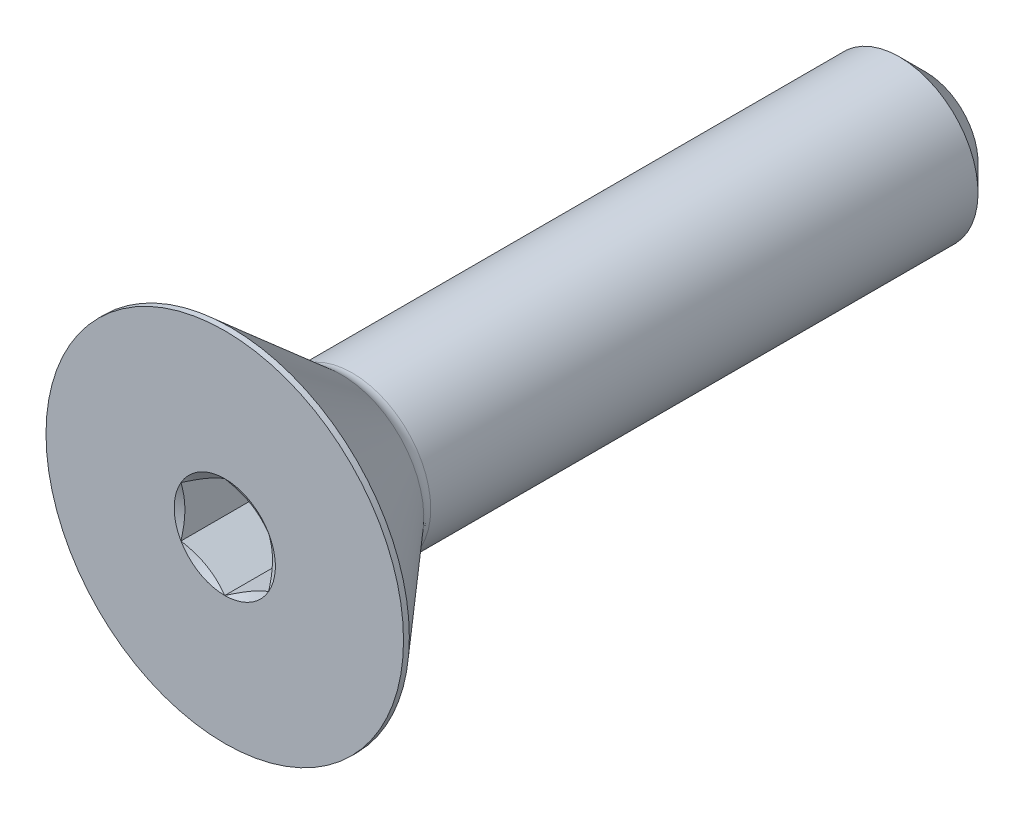
SolidWorks part; units mm, degrees
material "Plain Carbon Steel"
ref_plane "Front" through (0, 0, 0) normal (0, 0, 1) x (1, 0, 0)
ref_plane "Top" through (0, 0, 0) normal (0, 1, 0) x (1, 0, 0)
ref_plane "Right" through (0, 0, 0) normal (1, 0, 0) x (0, 0, -1)
sketch "Sketch1" plane through (0, 0, 0) normal (1, 0, 0) x (0, 0, -1)
  line L0 (0, 3.2385) -> (0.1054, 3.2385) construction
  line L1 (0.1054, 3.2385) -> (2.1082, 1.4975) construction
  line L2 (0, 1.4224) -> (12.7, 1.4224)
  line L3 (12.7, 1.4224) -> (12.7, 0)
  line L4 (12.7, 0) -> (0, 0)
  line L5 (0, 0) -> (0, 3.2385) construction
  line L6 (0, 3.2385) -> (0, -3.2385) construction
  line L7 (12.7, 1.4224) -> (12.7, -1.4224) construction
  line L8 (0, -3.2385) -> (0.1054, -3.2385) construction
  line L9 (0.1054, -3.2385) -> (2.1082, -1.4975) construction
  line L11 (0, 1.4224) -> (0, 0)
  line L12 (2.3091, 1.4224) -> (2.3091, 0) construction
  line L13 (-12.7, 0) -> (-12.7, 1.4224) construction
  arc A1 (2.1082, 1.4975) -> (2.3091, 1.4224) centre (2.3091, 1.7286) ccw construction
  dimension "D1" = 0.1054
  dimension "Min Thread" = 25.4
revolve "Revolve1" add sketch "Sketch1" angle 360 mid plane about L4
ref_plane "Plane2" through (0, 0, 12.7) normal (0, 0, 1) x (1, 0, 0)
chamfer "Chamfer1" distance 0.4763 angle 45 1 edges at (0, 1.4224, -12.7)
sketch "Sketch7" plane through (0, 0, 0) normal (1, 0, 0) x (0, 0, -1)
  line L0 (0, 3.2385) -> (0.1054, 3.2385) construction
  line L1 (0.1054, 3.2385) -> (2.1082, 1.4975) construction
  line L2 (0, 3.2385) -> (0.1054, 3.2385)
  line L3 (0.1054, 3.2385) -> (2.1082, 1.4975)
  line L4 (2.3091, 1.4224) -> (2.3091, 0) construction
  line L5 (2.3091, 1.4224) -> (2.3091, 0)
  line L7 (0, 0) -> (0, 3.2385) construction
  line L8 (0, 0) -> (0, 3.2385)
  line L9 (0, 0) -> (2.3091, 0)
  line L10 (6.985, 0) -> (-6.985, 0) construction
  arc A0 (2.1082, 1.4975) -> (2.3091, 1.4224) centre (2.3091, 1.7286) ccw construction
  arc A1 (2.1082, 1.4975) -> (2.3091, 1.4224) centre (2.3091, 1.7286) ccw
revolve "Revolve2" add sketch "Sketch7" angle 360 mid plane about L9
ref_plane "Plane1" through (0, 0, -2.3091) normal (0, 0, 1) x (1, 0, 0)
sketch "Sketch5" plane through (0, 0, 0) normal (0, 0, 1) x (1, 0, 0)
  line L0 (0, 0) -> (-0.9165, 0) construction
  line L1 (0, 0) -> (-2.7496, 1.5875) construction
  line L2 (0, 0) -> (-2.7496, -1.5875) construction
  line L6 (0, 0.9165) -> (0, 0.7559) construction
  line L7 (0, 0.7559) -> (0, 0.5953) construction
  line L9 (0, 0.9165) -> (-0.7937, 0.4583)
  line L10 (-0.7937, 0.4583) -> (-0.7937, -0.4583)
  line L11 (-0.7937, -0.4583) -> (0, -0.9165)
  line L12 (0, -0.9165) -> (0.7938, -0.4583)
  line L13 (0.7938, -0.4583) -> (0.7937, 0.4583)
  line L14 (0.7937, 0.4583) -> (0, 0.9165)
  circle A0 centre (0, 0) radius 0.9165 construction
  circle A1 centre (0, 0) radius 0.7559 construction
  circle A2 centre (0, 0) radius 0.5953 construction
  circle A3 centre (0, 0) radius 0.7937 construction
  dimension "D3" = 1.1906
  dimension "D4" = 30
  dimension "D5" = 30
extrude "Cut-Extrude2" cut sketch "Sketch5" against normal blind 1.4757
sketch "Sketch6" plane through (0, 0, 0) normal (0, 0, 1) x (1, 0, 0)
  circle A0 centre (0, 0) radius 0.9165
extrude "Cut-Extrude3" cut sketch "Sketch6" against normal blind 1.4757 draft 60
sketch "Sketch9" [suppressed] plane through (0, 0, -3.6076) normal (0, 0, 1) x (1, 0, 0)
  circle A1 centre (0, 0) radius 2.413
  circle A2 centre (0, 0) radius 2.413
  point P0 (0, 2.413)
  dimension "D1" = 0
extrude "Boss-Extrude2" [suppressed] add sketch "Sketch9" against normal up to surface (15.4424 mm away)
equation "\"D1@Cut-Extrude2\" = \"Head Ht@Sketch1\" * .7"
equation "\"D1@Sketch1\" = \"Head Ht@Sketch1\" * .05"
equation "\"D1@Cut-Extrude3\" = \"D1@Cut-Extrude2\""
equation "\"D3@Sketch5\" = \"Hex@Sketch5\" * .75"
